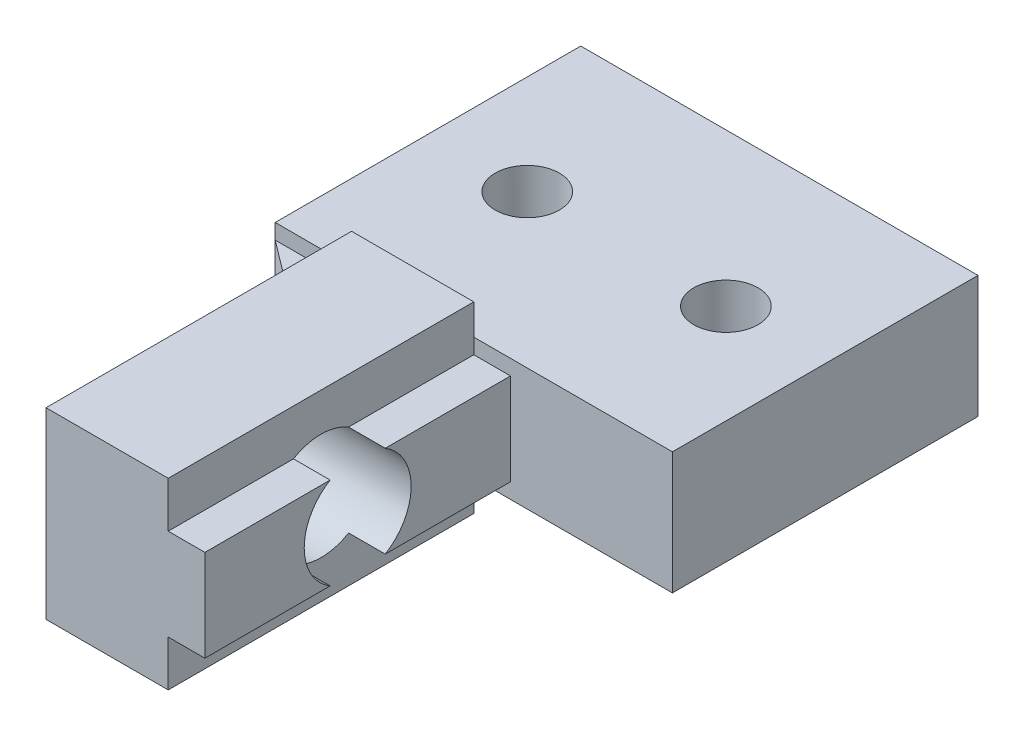
SolidWorks part; units mm, degrees
ref_plane "前视基准面" through (0, 0, 0) normal (0, 0, 1) x (1, 0, 0)
ref_plane "上视基准面" through (0, 0, 0) normal (0, 1, 0) x (1, 0, 0)
ref_plane "右视基准面" through (0, 0, 0) normal (1, 0, 0) x (0, 0, -1)
sketch "草图2" plane through (0, 0, 0) normal (0, 1, 0) x (1, 0, 0)
  line L2 (-3.25, 0) -> (3.25, 0) construction
  line L7 (-6.5, 5) -> (6.5, 5)
  line L8 (-6.5, 5) -> (-6.5, -5)
  line L10 (-6.5, -5) -> (6.5, -5)
  line L11 (6.5, 5) -> (6.5, -5)
  line L12 (-6.5, 5) -> (6.5, -5) construction
  line L13 (-6.5, -5) -> (6.5, 5) construction
  circle A0 centre (-3.25, 0) radius 1.05
  circle A1 centre (3.25, 0) radius 1.05
  point P4 (0, 0)
  dimension "D1" = 2.1
  dimension "D2" = 6.5
  dimension "D3" = 13
  dimension "D4" = 10
extrude "凸台-拉伸1" add sketch "草图2" along normal blind 6
sketch "草图3" plane through (0, 0, 5) normal (0, 0, 1) x (1, 0, 0)
  line L0 (0, 6) -> (0, 4.5)
  line L1 (-6.5, 6) -> (6.5, 6) construction
  line L2 (0, 4.5) -> (1.2, 4.5)
  line L3 (1.2, 4.5) -> (1.2, 1.5)
  line L4 (1.2, 1.5) -> (0, 1.5)
  line L5 (0, 1.5) -> (0, 0)
  line L6 (0, 0) -> (-4, 0)
  line L7 (-6.5, 0) -> (6.5, 0) construction
  line L8 (-4, 0) -> (-4, 6)
  line L9 (-4, 6) -> (0, 6)
  line L10 (1.2, 3) -> (6.5, 3) construction
  line L11 (6.5, 6) -> (6.5, 0) construction
  dimension "D1" = 3
  dimension "D2" = 1.2
  dimension "D3" = 4
extrude "凸台-拉伸2" add sketch "草图3" along normal blind 10
sketch "草图4" plane through (0, 6, 0) normal (0, 1, 0) x (1, 0, 0)
  line L1 (-6.5, 5) -> (6.5, 5)
  line L2 (-6.5, 5) -> (-6.5, -5)
  line L3 (-6.5, -5) -> (6.5, -5)
  line L4 (6.5, 5) -> (6.5, -5)
extrude "切除-拉伸1" cut sketch "草图4" against normal blind 1
sketch "草图5" plane through (0, 0, 0) normal (0, -1, 0) x (1, 0, 0)
  line L1 (-6.5, 5) -> (6.5, 5)
  line L2 (-6.5, 5) -> (-6.5, -5)
  line L3 (-6.5, -5) -> (6.5, -5)
  line L4 (6.5, 5) -> (6.5, -5)
extrude "切除-拉伸2" cut sketch "草图5" against normal blind 1
sketch "草图6" plane through (-4, 0, 0) normal (-1, 0, 0) x (0, 0, 1)
  line L0 (5, 6) -> (5, 5) construction
  line L1 (15, 6) -> (15, 0) construction
  circle A0 centre (10, 3) radius 1.75
  point P4 (0, 0)
  point P7 (15, 3)
  dimension "D1" = 3.5
  dimension "D2" = 5
extrude "切除-拉伸3" cut sketch "草图6" against normal through all
sketch "草图7" plane through (0, 1.5, 0) normal (0, -1, 0) x (1, 0, 0)
  line L0 (-6.5, 5) -> (-3.8458, 7)
  point P3 (0, 0)
  point P4 (0, 0)
  dimension "D1" = 2
rib "筋1" sketch "草图7" sketch "草图7" thickness 3 extrusion direction parallel to sketch draft on no parameters "D1"=3
